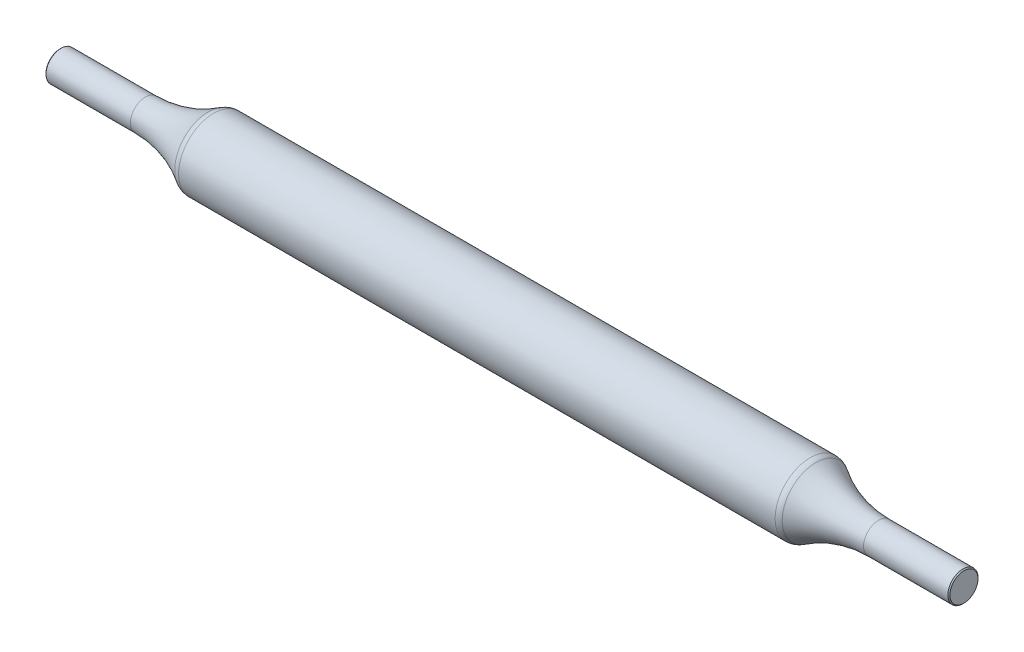
SolidWorks part; units mm, degrees
ref_plane "Front Plane" through (0, 0, 0) normal (0, 0, 1) x (1, 0, 0)
ref_plane "Top Plane" through (0, 0, 0) normal (0, 1, 0) x (1, 0, 0)
ref_plane "Right Plane" through (0, 0, 0) normal (1, 0, 0) x (0, 0, -1)
sketch "Sketch1" plane through (0, 0, 0) normal (0, 0, 1) x (1, 0, 0)
  line L0 (-22.5, 0) -> (22.5, 0)
  line L1 (-22.5, 0) -> (-22.5, 0.75)
  line L2 (-22.5, 0.75) -> (-18.25, 0.75)
  line L3 (22.5, 0) -> (22.5, 0.75)
  line L4 (22.5, 0.75) -> (18.25, 0.75)
  line L5 (-15, 1.75) -> (15, 1.75)
  arc A0 (-18.25, 0.75) -> (-15, 1.75) centre (-18.25, 6.5312) ccw
  arc A1 (15, 1.75) -> (18.25, 0.75) centre (18.25, 6.5313) ccw
  point P2 (0, 0)
  point P10 (0, 1.75)
  dimension "D1" = 45
  dimension "D2" = 30
  dimension "D3" = 4.25
  dimension "D4" = 1.75
  dimension "D5" = 0.75
revolve "Revolve1" add sketch "Sketch1" angle 360 about L0
fillet "Fillet1" radius 0.5 2 edges at (-15, -1.75, 0) (15, -1.75, 0)
chamfer "Chamfer1" distance 0.05 angle 45 2 edges at (22.5, -0.75, 0) (-22.5, -0.75, 0)
